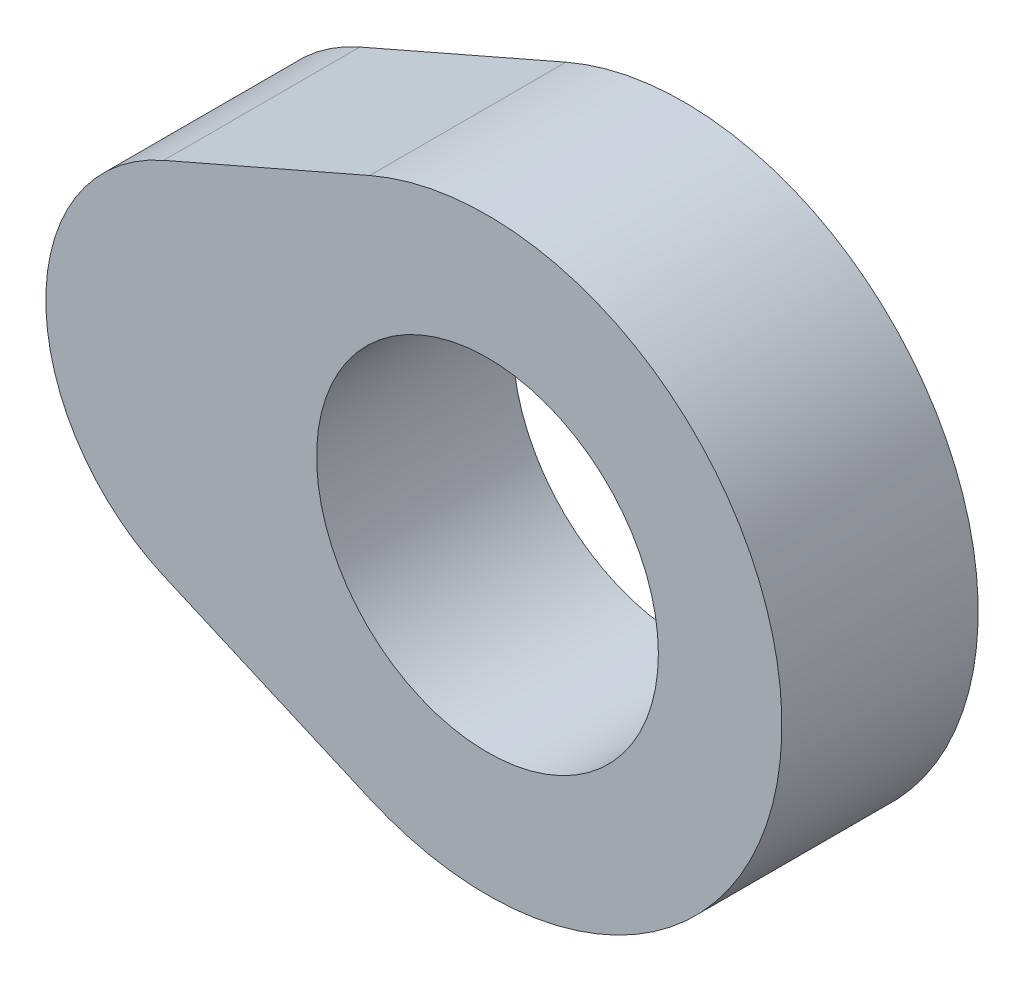
SolidWorks part; units mm, degrees
ref_plane "Front Plane" through (0, 0, 0) normal (0, 0, 1) x (1, 0, 0)
ref_plane "Top Plane" through (0, 0, 0) normal (0, 1, 0) x (1, 0, 0)
ref_plane "Right Plane" through (0, 0, 0) normal (1, 0, 0) x (0, 0, -1)
sketch "Sketch1" plane through (0, 0, 0) normal (0, 0, 1) x (1, 0, 0)
  line L0 (0, 0) -> (-30, 51.9615) construction
  line L1 (0, 0) -> (-60, 0) construction
  line L2 (0, 0) -> (-30, -51.9615) construction
  line L3 (-66, 36.6606) -> (-24, 54.9909)
  line L4 (-66, -36.6606) -> (-24, -54.9909)
  circle A1 centre (0, 0) radius 34.8236
  arc A3 (-24, -54.9909) -> (-24, 54.9909) centre (0, 0) ccw
  arc A4 (-66, -36.6606) -> (-66, 36.6606) centre (-50, 0) cw
  point P4 (-150, 0)
  point P9 (-75, 0)
  dimension "D1" = 60
  dimension "D3" = 120
  dimension "D4" = 150
  dimension "D5" = 40
  dimension "D2" = 60
extrude "Boss-Extrude1" add sketch "Sketch1" along normal mid plane 40
